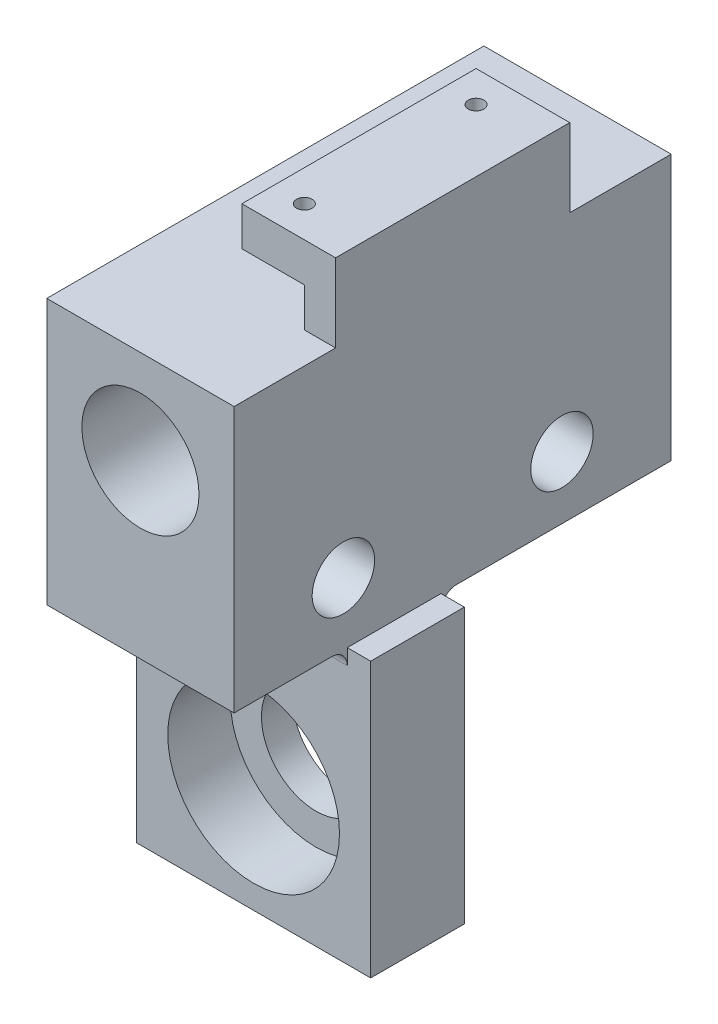
SolidWorks part; units mm, degrees
ref_plane "Front Plane" through (0, 0, 0) normal (0, 0, 1) x (1, 0, 0)
ref_plane "Top Plane" through (0, 0, 0) normal (0, 1, 0) x (1, 0, 0)
ref_plane "Right Plane" through (0, 0, 0) normal (1, 0, 0) x (0, 0, -1)
sketch "Sketch1" plane through (0, 0, 0) normal (0, 0, 1) x (1, 0, 0)
  line L1 (-12, 12) -> (12, 12)
  line L2 (-12, 12) -> (-12, -22)
  line L3 (-12, -22) -> (12, -22)
  line L4 (12, 12) -> (12, -22)
  circle A0 centre (0, 0) radius 7.5
  dimension "D1" = 12
  dimension "D5" = 15
  dimension "D2" = 24
  dimension "D3" = 12
  dimension "D4" = 34
extrude "Boss-Extrude1" add sketch "Sketch1" along normal mid plane 56
sketch "Sketch3" plane through (0, -22, 0) normal (0, -1, 0) x (1, 0, 0)
  line L1 (-15, 13.5) -> (15, 13.5)
  line L2 (-15, 13.5) -> (-15, 1.5)
  line L3 (-15, 1.5) -> (15, 1.5)
  line L4 (15, 13.5) -> (15, 1.5)
  dimension "D1" = 30
  dimension "D2" = 15
  dimension "D3" = 13.5
  dimension "D4" = 12
extrude "Boss-Extrude2" add sketch "Sketch3" along normal blind 35.15
sketch "Sketch4" plane through (0, 0, 13.5) normal (0, 0, 1) x (1, 0, 0)
  line L0 (15, -57.15) -> (-15, -57.15) construction
  line L1 (15, -57.15) -> (15, -22) construction
  circle A0 centre (0, -43.15) radius 11
  dimension "D1" = 22
  dimension "D2" = 14
  dimension "D3" = 15
extrude "Cut-Extrude2" cut sketch "Sketch4" against normal blind 8
fillet "Fillet1" radius 2 2 edges at (0, -22, 1.5) (0, -22, 13.5)
sketch "Sketch5" plane through (0, 12, 0) normal (0, 1, 0) x (1, 0, 0)
  line L0 (12, -28) -> (12, 28) construction
  line L1 (0, 15) -> (12, 15)
  line L2 (0, 15) -> (0, -15)
  line L3 (0, -15) -> (12, -15)
  line L4 (12, 15) -> (12, -15)
  point P6 (12, 0)
  dimension "D1" = 30
  dimension "D2" = 12
extrude "Boss-Extrude3" add sketch "Sketch5" along normal blind 10
sketch "Sketch6" plane through (0, 0, 15) normal (0, 0, 1) x (1, 0, 0)
  line L0 (0, 22) -> (0, 12) construction
  line L1 (0, 17) -> (8, 17)
  line L2 (0, 17) -> (0, 12)
  line L3 (0, 12) -> (8, 12)
  line L4 (8, 17) -> (8, 12)
  line L5 (0, 12) -> (12, 12) construction
  dimension "D1" = 8
  dimension "D2" = 5
extrude "Cut-Extrude3" cut sketch "Sketch6" against normal through all
sketch "Sketch7" plane through (0, 22, 0) normal (0, 1, 0) x (1, 0, 0)
  line L0 (0, -15) -> (12, -15) construction
  line L1 (0, 15) -> (0, -15) construction
  line L3 (12, 15) -> (0, 15) construction
  circle A0 centre (4, 11) radius 1
  circle A1 centre (4, -11) radius 1
  dimension "D1" = 2
  dimension "D2" = 4
  dimension "D3" = 4
  dimension "D4" = 4
  dimension "D5" = 4
extrude "Cut-Extrude4" cut sketch "Sketch7" against normal up to next
sketch "Sketch8" plane through (12, 0, 0) normal (1, 0, 0) x (0, 0, -1)
  line L2 (-28, -22) -> (-15.5, -22) construction
  circle A0 centre (-14, -14) radius 4
  circle A1 centre (14, -14) radius 4
  point P4 (0, 0)
  dimension "D1" = 8
  dimension "D2" = 28
  dimension "D4" = 8
  dimension "D5" = 14
extrude "Cut-Extrude5" cut sketch "Sketch8" against normal blind 20
sketch "Sketch9" plane through (0, 0, 5.5) normal (0, 0, 1) x (1, 0, 0)
  circle A0 centre (0, -43.15) radius 7
  circle A1 centre (0, -43.15) radius 11 construction
  dimension "D1" = 14
extrude "Cut-Extrude6" cut sketch "Sketch9" against normal blind 10
